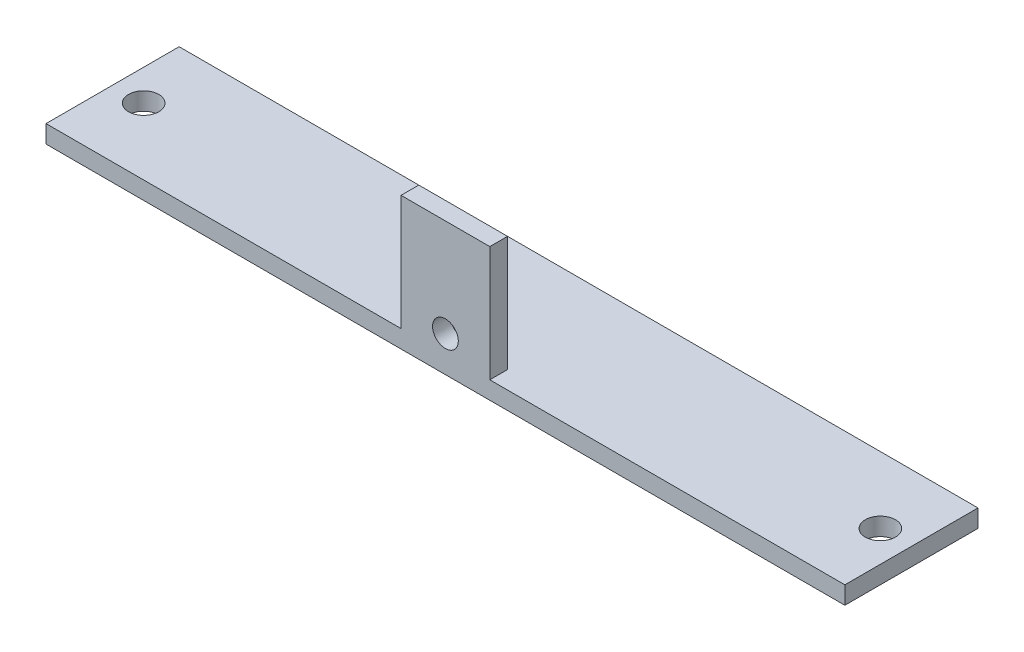
SolidWorks part; units mm, degrees
ref_plane "Plan de face" through (0, 0, 0) normal (0, 0, 1) x (1, 0, 0)
ref_plane "Plan de dessus" through (0, 0, 0) normal (0, 1, 0) x (1, 0, 0)
ref_plane "Plan de droite" through (0, 0, 0) normal (1, 0, 0) x (0, 0, -1)
sketch "Esquisse1" plane through (0, 0, 0) normal (0, 1, 0) x (1, 0, 0)
  line L1 (-45, -7.5) -> (45, -7.5)
  line L2 (-45, -7.5) -> (-45, 7.5)
  line L3 (-45, 7.5) -> (45, 7.5)
  line L4 (45, -7.5) -> (45, 7.5)
  line L5 (-45, -7.5) -> (45, 7.5) construction
  line L6 (-45, 7.5) -> (45, -7.5) construction
  point P0 (0, 0)
  dimension "D1" = 90
  dimension "D2" = 15
extrude "Boss.-Extru.1" add sketch "Esquisse1" along normal blind 15
sketch "Esquisse2" plane through (-45, 0, 0) normal (-1, 0, 0) x (0, 0, 1)
  line L0 (-7.5, 0) -> (7.5, 0) construction
  line L1 (-7.5, 15) -> (5.5, 15)
  line L2 (-7.5, 15) -> (-7.5, 2)
  line L3 (-7.5, 2) -> (5.5, 2)
  line L4 (5.5, 15) -> (5.5, 2)
  line L5 (7.5, 15) -> (7.5, 0) construction
  dimension "D1" = 2
  dimension "D2" = 2
extrude "Enlèv. mat.-Extru.1" cut sketch "Esquisse2" against normal through all
hole_wizard "Dégagement M31" positions "Esquisse4" profile "Esquisse3" hole size "M3" standard "Iso"
sketch "Esquisse4" plane through (0, 2, 0) normal (0, 1, 0) x (1, 0, 0)
  line L0 (-41.5, 0) -> (-45, 0) construction
  line L1 (-45, 7.5) -> (-45, -5.5) construction
  line L3 (41.5, 0) -> (45, 0) construction
  line L4 (45, 7.5) -> (45, -5.5) construction
  point P0 (-41.5, 0)
  point P2 (41.5, 0)
  dimension "D1" = 83
sketch "Esquisse3" plane through (-41.5, 2, 0) normal (1, 0, 0) x (0, 0, 1)
  line L0 (0, 0) -> (0, 25.0215)
  line L1 (0, 25.0215) -> (1.7, 24)
  line L2 (1.7, 24) -> (1.7, 0)
  line L5 (1.7, 0) -> (0, 0)
  line L10 (0, 25.0215) -> (-1.7, 24) construction
  line L11 (0, -6.35) -> (0, 107.95) construction
  dimension "Diamètre du perçage" = 3.4
  dimension "Profondeur du perçage" = 24
  dimension "Angle de pointe" = 118
sketch "Esquisse5" plane through (0, 0, 5.5) normal (0, 0, -1) x (-1, 0, 0)
  line L0 (-45, 2) -> (45, 2) construction
  line L1 (45, 15) -> (5, 15)
  line L2 (45, 15) -> (45, 2)
  line L3 (45, 2) -> (5, 2)
  line L4 (5, 15) -> (5, 2)
  line L5 (-45, 2) -> (45, 2) construction
  line L6 (-45, 15) -> (-5, 15)
  line L7 (-45, 15) -> (-45, 2)
  line L8 (-45, 2) -> (-5, 2)
  line L9 (-5, 15) -> (-5, 2)
  dimension "D1" = 10
extrude "Enlèv. mat.-Extru.2" cut sketch "Esquisse5" against normal through all
hole_wizard "Dégagement M2.51" positions "Esquisse10" profile "Esquisse9" hole size "M2.5" standard "Iso"
sketch "Esquisse10" plane through (0, 0, 5.5) normal (0, 0, -1) x (-1, 0, 0)
  line L0 (-5, 2) -> (5, 2) construction
  line L2 (5, 4) -> (0, 4) construction
  line L3 (5, 15) -> (5, 2) construction
  line L4 (0, 4) -> (-5, 4) construction
  line L5 (-5, 2) -> (-5, 15) construction
  point P0 (0, 4)
  dimension "D1" = 2
sketch "Esquisse9" plane through (0, 4, 5.5) normal (1, 0, 0) x (0, 1, 0)
  line L0 (0, 0) -> (0, 24.8712)
  line L1 (0, 24.8712) -> (1.45, 24)
  line L2 (1.45, 24) -> (1.45, 0)
  line L5 (1.45, 0) -> (0, 0)
  line L10 (0, 24.8712) -> (-1.45, 24) construction
  line L11 (0, -6.35) -> (0, 107.95) construction
  dimension "Diamètre du perçage" = 2.9
  dimension "Profondeur du perçage" = 24
  dimension "Angle de pointe" = 118
